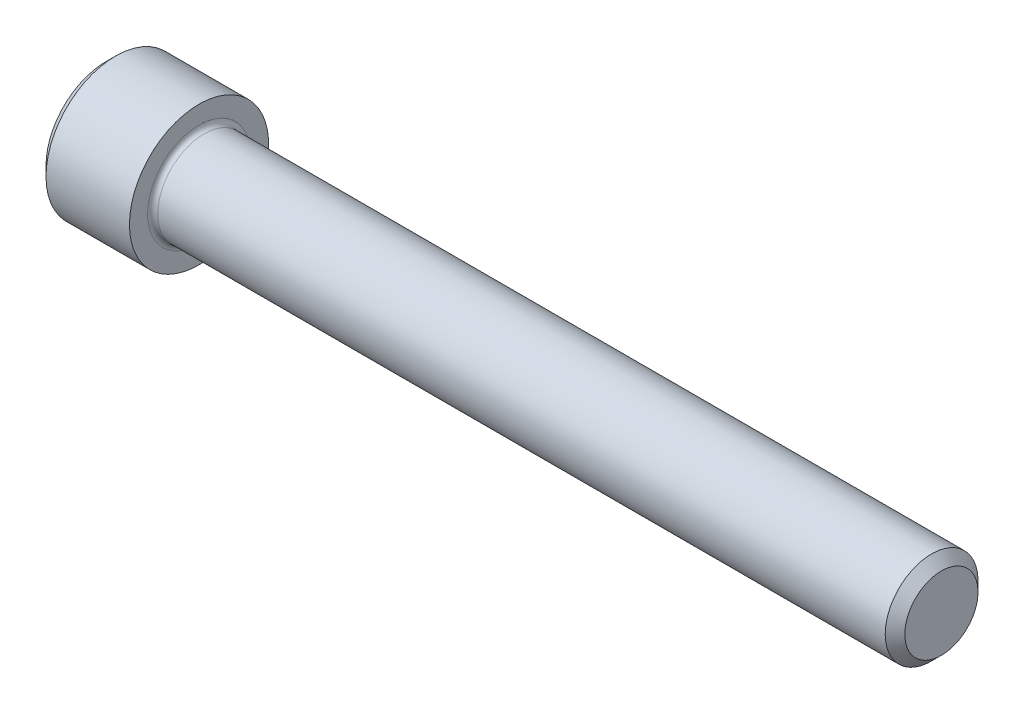
SolidWorks part; units mm, degrees
ref_plane "Plane1" through (0, 0, 0) normal (0, 0, 1) x (1, 0, 0)
ref_plane "Plane2" through (0, 0, 0) normal (0, 1, 0) x (1, 0, 0)
ref_plane "Plane3" through (0, 0, 0) normal (1, 0, 0) x (0, 0, -1)
sketch "BodySke" plane through (0, 0, 0) normal (0, 0, 1) x (1, 0, 0)
  line L0 (0, 0) -> (0, 5.1537)
  line L1 (0.8001, 5.9538) -> (7.9375, 5.9538)
  line L2 (7.9375, 5.9538) -> (7.9375, 3.9688)
  line L3 (7.9375, 3.9688) -> (70.598, 3.9687)
  line L4 (71.4375, 3.1293) -> (71.4375, 0)
  line L5 (71.4375, 0) -> (0, 0)
  line L6 (-31.75, 0) -> (127, 0) construction
  line L7 (0, 5.1537) -> (0.8001, 5.9538)
  line L8 (71.4375, 3.1293) -> (70.598, 3.9687)
  line L9 (0, -5.1537) -> (0.8001, -5.9538) construction
  line L10 (71.4375, -3.1293) -> (70.598, -3.9688) construction
  line L11 (9.3472, 9.525) -> (9.3472, 3.175) construction
  line L12 (7.9375, 9.525) -> (7.9375, 3.175) construction
  line L13 (33.3375, 9.525) -> (33.3375, 3.175) construction
  dimension "Diameter" = 7.9375
  dimension "Head_ht" = 7.9375
  dimension "Length" = 63.5
  dimension "Body_ch_ang" = 45
  dimension "Head_dia" = 11.9075
  dimension "Head_ch_ang" = 45
  dimension "Head_side_ht" = 7.1374
  dimension "Minor_dia" = 6.2586
  dimension "Advance" = 1.4097
  dimension "Thread_nom" = 63.5
  dimension "Thread_length" = 38.1
revolve "Base-Revolve" add sketch "BodySke" angle 360 about L6
cosmetic thread "ThreadCosmetic" [suppressed] parameters "Thread_length"=62.0903, "Thread_minor"=6.2586
fillet "Fillet1" radius 0.4318 1 edges at (7.9375, 0, 3.9688)
sketch "Sketch2" plane through (0, 0, 0) normal (0, 0, 1) x (1, 0, 0)
  line L0 (0, 3.175) -> (3.8354, 3.175)
  line L1 (3.8354, 3.175) -> (5.6685, 0)
  line L2 (-31.75, 0) -> (127, 0) construction
  line L3 (5.6685, 0) -> (0, 0)
  line L4 (0, 0) -> (0, 3.175)
  line L5 (0, 5.1537) -> (0, -5.1537) construction
  line L6 (0, 0) -> (47.625, 0) construction
  line L7 (7.9375, -5.9538) -> (7.9375, 5.9538) construction
  dimension "D1" = 3.175
  dimension "D2" = 60
  dimension "Wall_thickness" = 4.1021
revolve "Hex-PreBroach" cut sketch "Sketch2" angle 360 about L6
sketch "Sketch3" plane through (0, 0, 0) normal (-1, 0, 0) x (0, 0.5, 0.866)
  line L0 (1.8331, 3.175) -> (-1.8331, 3.175)
  line L1 (-1.8331, 3.175) -> (-3.6662, 0)
  line L2 (1.8331, 3.175) -> (3.6662, 0)
  line L3 (1.8331, -3.175) -> (3.6662, 0)
  line L4 (1.8331, -3.175) -> (-1.8331, -3.175)
  line L5 (-1.8331, -3.175) -> (-3.6662, 0)
  dimension "D1" = 3.175
  dimension "D2" = 3.175
  dimension "Hex_size" = 6.35
extrude "Hex" cut sketch "Sketch3" against normal blind 3.8354
sketch "Sketch4" plane through (0, 0, 0) normal (-1, 0, 0) x (0, 0, 1)
  line L0 (0, 0) -> (3.7846, 0)
  line L1 (0, 0) -> (6.1484, 3.5498) construction
  line L2 (0, 0) -> (1.8923, 3.2776)
  line L3 (3.1235, 0.8061) -> (3.6229, 1.0945)
  line L4 (2.2599, 2.3019) -> (2.7593, 2.5903)
  arc A0 (3.1235, 0.8061) -> (2.2599, 2.3019) centre (0, 0) ccw
  arc A1 (3.7846, 0) -> (3.6229, 1.0945) centre (0, 0) ccw
  arc A2 (1.8923, 3.2776) -> (2.7593, 2.5903) centre (0, 0) cw
  dimension "D1" = 30
  dimension "Spline_n_dim" = 6.4516
  dimension "Spline_m_dim" = 7.5692
  dimension "D2" = 60
  dimension "D3" = 0.8636
  dimension "Spline_p_dim" = 1.7272
extrude "Spline" [suppressed] cut sketch "Sketch4" against normal blind 3.8354
pattern_circular "CirPattern1" [suppressed] count 6 every 60 about axis through (-31.75, 0, 0) along (1, 0, 0)
sketch "Sketch5" plane through (0, 0, 0) normal (0, 0, 1) x (1, 0, 0)
  line L0 (-31.75, 0) -> (127, 0) construction
  line L2 (0, 5.1537) -> (0, -5.1537) construction
  circle A0 centre (2.6416, 0) radius 0.5905
  dimension "Drilled_hole_dia" = 1.1811
  dimension "Drilled_hole_loc" = 2.6416
extrude "Hole" [suppressed] cut sketch "Sketch5" against normal through all and the other way through all
pattern_circular "Drilled-4" [suppressed] count 2 every 60 about axis through (-31.75, 0, 0) along (1, 0, 0)
pattern_circular "Drilled-6" [suppressed] count 3 every 60 about axis through (-31.75, 0, 0) along (1, 0, 0)
sketch "ThdSchSke" [suppressed] plane through (0, 0, 0) normal (0, 0, 1) x (1, 0, 0)
  line L0 (63.5, -11.4313) -> (62.6116, -12.7)
  line L1 (63.5, -11.4313) -> (64.3884, -12.7)
  line L2 (64.3884, -12.7) -> (64.3884, -15.875)
  line L3 (-3.175, 0) -> (5.1513, 0) construction
  line L5 (64.3884, -15.875) -> (62.6116, -15.875)
  line L6 (62.6116, -15.875) -> (62.6116, -12.7)
  line L7 (0, 16.51) -> (0, -16.51) construction
  dimension "Thread_minor" = 6.2586
  dimension "Diameter" = 7.9375
  dimension "Start" = 9.3472
  dimension "SideAngle" = 55
  dimension "VeeAngle" = 70
  dimension "Overcut" = 9.9219
revolve "ThreadSchematic" [suppressed] cut sketch "ThdSchSke" angle 360 about L3
pattern_linear "ThdSchPat" [suppressed]
equation "\"D2@Sketch3\" = \"Hex_size@Sketch3\" / 2"
equation "\"D1@Sketch3\" = \"Hex_size@Sketch3\" / 2"
equation "\"D1@Sketch2\" = \"Hex_size@Sketch3\" / 2"
equation "\"D3@Sketch4\" = \"Spline_p_dim@Sketch4\" / 2"
equation "\"Thread_minor@ThreadCosmetic\"  =  \"Minor_dia@BodySke\""
equation "\"D2@CirPattern1\" = 360 / \"Num_teeth@CirPattern1\""
equation "\"Wall_thickness@Sketch2\" = \"Head_ht@BodySke\" - \"Key_eng@Hex\""
equation "\"Thread_length@ThreadCosmetic\" = ((sgn( (\"Length@BodySke\" - \"Advance@BodySke\" ) - \"Thread_nom@BodySke\" )-1)*( (\"Length@BodySke\" - \"Advance@BodySke\" ) - \"Thread_nom@BodySke\" ))/-2+ \"Thread_nom@BodySke\""
equation "\"Thread_minor@ThdSchSke\" = \"Minor_dia@BodySke\""
equation "\"Diameter@ThdSchSke\" = \"Diameter@BodySke\""
equation "\"Overcut@ThdSchSke\" = \"Diameter@BodySke\" * 1.25"
equation "\"Start@ThdSchSke\" = \"Head_ht@BodySke\" + \"Length@BodySke\" - \"Thread_length@ThreadCosmetic\"  '---Non-countersunk---"
equation "\"Num_threads@ThdSchPat\" = int( \"Thread_length@ThreadCosmetic\" / \"Advance@BodySke\" + 0.999 )  + 1"
equation "\"Advance@ThdSchPat\" = \"Thread_length@ThreadCosmetic\" /  (\"Num_threads@ThdSchPat\" - 1) 'relax it"
equation "\"Num_threads@ThdSchPat\" = \"Num_threads@ThdSchPat\" - sgn( \"Num_threads@ThdSchPat\" - 1) '---chamfered tips only---"
